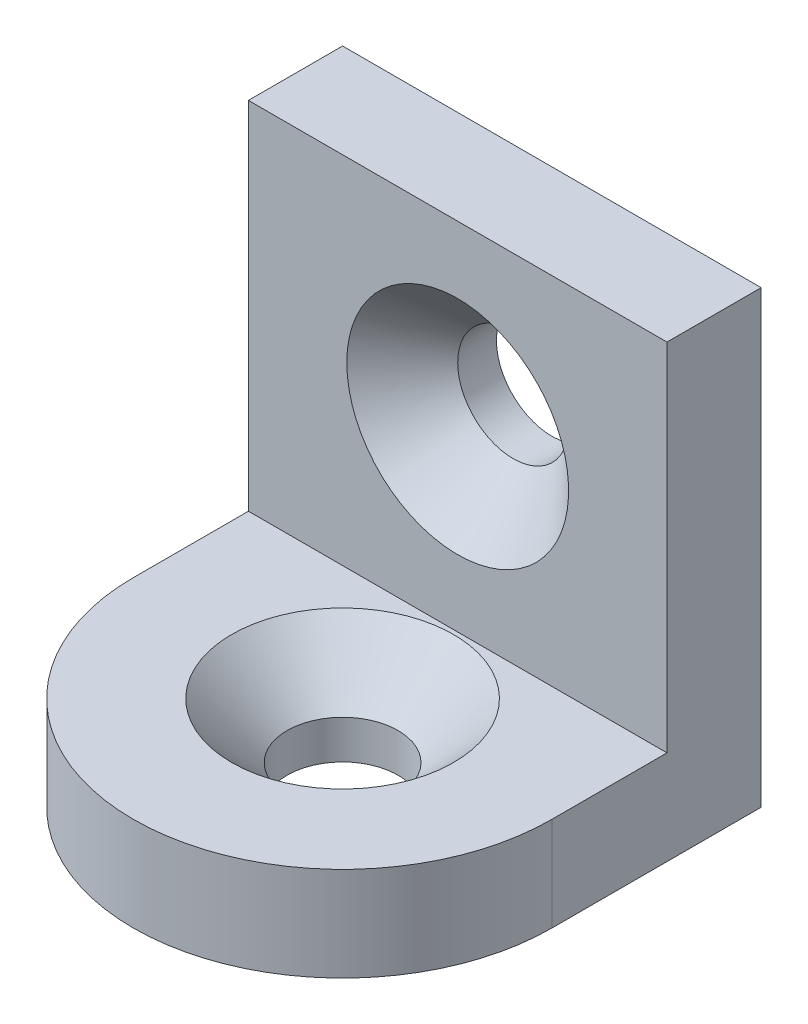
SolidWorks part; units mm, degrees
material "6061 合金"
ref_plane "前视基准面" through (0, 0, 0) normal (0, 0, 1) x (1, 0, 0)
ref_plane "上视基准面" through (0, 0, 0) normal (0, 1, 0) x (1, 0, 0)
ref_plane "右视基准面" through (0, 0, 0) normal (1, 0, 0) x (0, 0, -1)
sketch "草图1" plane through (0, 0, 0) normal (0, 1, 0) x (1, 0, 0)
  line L1 (-10, 10) -> (10, 10)
  line L2 (-10, 10) -> (-10, -10)
  line L3 (-10, -10) -> (10, -10)
  line L4 (10, 10) -> (10, -10)
  line L5 (-10, 10) -> (10, -10) construction
  line L6 (-10, -10) -> (10, 10) construction
  circle A0 centre (0, 0) radius 10
  circle A1 centre (0, 0) radius 2.65
  point P0 (0, 0)
  dimension "D3" = 5.3
  dimension "D1" = 20
  dimension "D2" = 20
extrude "凸台-拉伸1" add sketch "草图1" along normal blind 4.5 contours A0 L1 L2 | A0 L4 L1 | A0 A1
ref_plane "基准面1" through (0, 4.5, 0) normal (0, 1, 0) x (1, 0, 0)
sketch "草图2" plane through (0, 4.5, 0) normal (0, 1, 0) x (1, 0, 0)
  line L0 (10, 10) -> (10, 0) construction
  line L1 (-10, 10) -> (10, 10)
  line L2 (-10, 10) -> (-10, 5.5)
  line L3 (-10, 5.5) -> (10, 5.5)
  line L4 (10, 10) -> (10, 5.5)
  dimension "D1" = 4.5
extrude "凸台-拉伸2" add sketch "草图2" along normal blind 17
ref_plane "基准面2" through (0, 0, -5.5) normal (0, 0, 1) x (1, 0, 0)
sketch "草图3" plane through (0, 0, -5.5) normal (0, 0, 1) x (1, 0, 0)
  line L0 (-10, 21.5) -> (10, 4.5) construction
  circle A0 centre (0, 13) radius 2.65
  dimension "D1" = 5.3
extrude "切除-拉伸1" cut sketch "草图3" against normal blind 17
chamfer "倒角1" distance 2.65 angle 45 2 edges at (2.65, 13, -5.5) (0, 4.5, 2.65)
